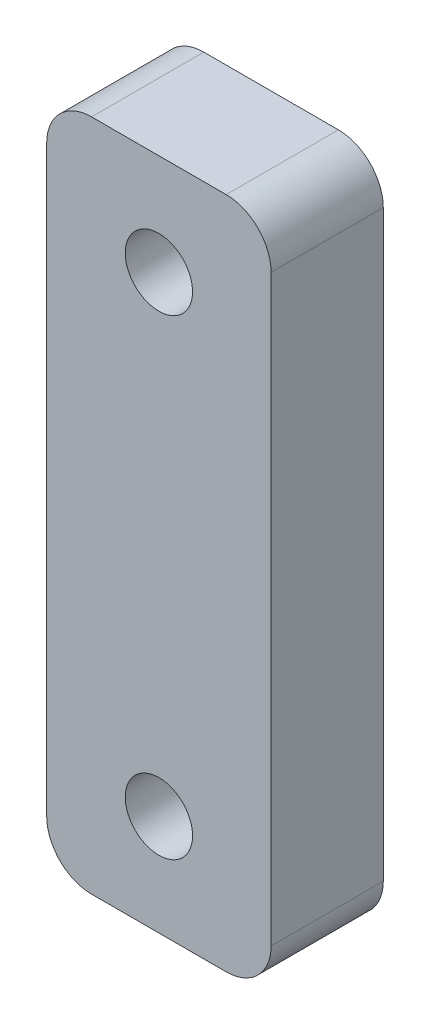
SolidWorks part; units mm, degrees
ref_plane "前视基准面" through (0, 0, 0) normal (0, 0, 1) x (1, 0, 0)
ref_plane "上视基准面" through (0, 0, 0) normal (0, 1, 0) x (1, 0, 0)
ref_plane "右视基准面" through (0, 0, 0) normal (1, 0, 0) x (0, 0, -1)
sketch "草图2" plane through (0, 0, 0) normal (0, 0, 1) x (1, 0, 0)
  line L1 (5, -15) -> (-5, -15)
  line L2 (5, -15) -> (5, 15)
  line L3 (5, 15) -> (-5, 15)
  line L4 (-5, -15) -> (-5, 15)
  line L5 (5, -15) -> (-5, 15) construction
  line L6 (5, 15) -> (-5, -15) construction
  point P0 (0, 0)
  dimension "D1" = 10
  dimension "D2" = 30
extrude "凸台-拉伸1" add sketch "草图2" along normal blind 5
sketch "草图3" plane through (0, 0, 5) normal (0, 0, 1) x (1, 0, 0)
  line L0 (0, -15) -> (0, -10.5) construction
  line L1 (-5, -15) -> (5, -15) construction
  line L2 (0, 0) -> (5, 0) construction
  line L3 (5, -15) -> (5, 15) construction
  line L4 (0, 15) -> (0, 10.5) construction
  circle A0 centre (0, -10.5) radius 1.5
  circle A1 centre (0, 10.5) radius 1.5
  dimension "D1" = 3
  dimension "D2" = 4.5
extrude "切除-拉伸1" cut sketch "草图3" against normal through all
fillet "圆角1" radius 2 4 edges at (5, -15, 2.5) (-5, -15, 2.5) (5, 15, 2.5) (-5, 15, 2.5)
